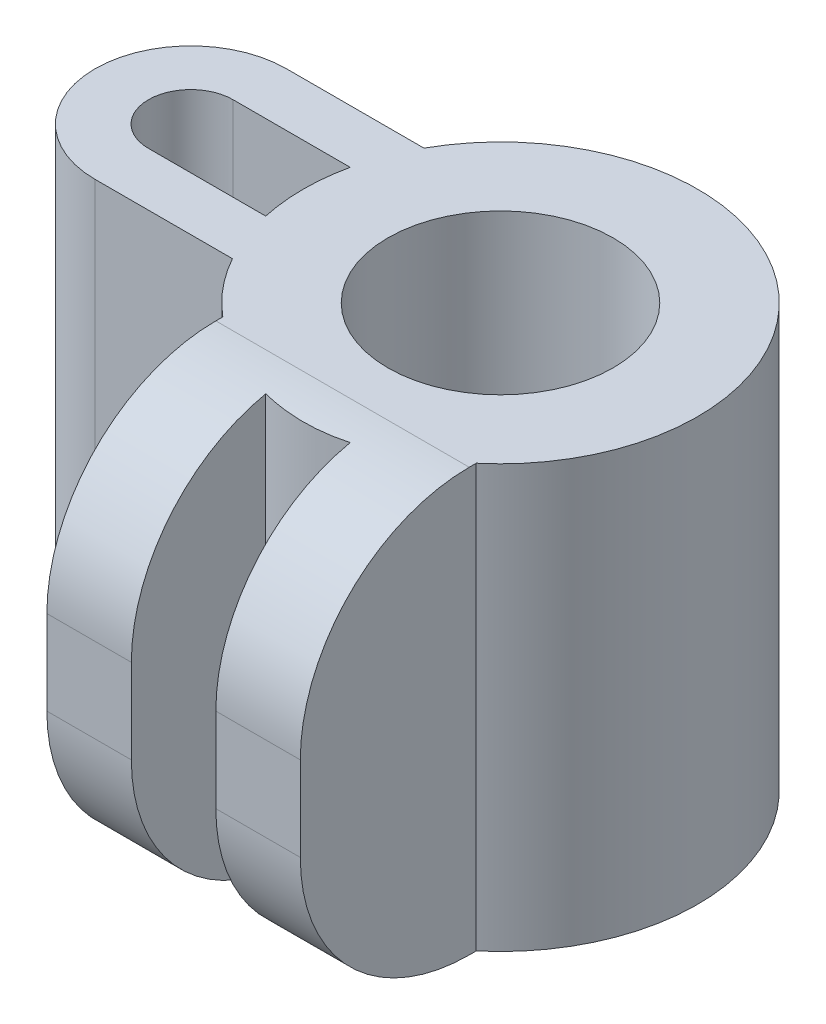
SolidWorks part; units mm, degrees
ref_plane "Front Plane" through (0, 0, 0) normal (0, 0, 1) x (1, 0, 0)
ref_plane "Top Plane" through (0, 0, 0) normal (0, 1, 0) x (1, 0, 0)
ref_plane "Right Plane" through (0, 0, 0) normal (1, 0, 0) x (0, 0, -1)
sketch "Sketch1" plane through (0, 0, 0) normal (0, 1, 0) x (1, 0, 0)
  line L0 (-55, 7.5) -> (-34.187, 7.5)
  line L1 (-55, -7.5) -> (-34.187, -7.5)
  line L2 (-55, -17) -> (-30.5941, -17)
  line L3 (-55, 17) -> (-30.5941, 17)
  line L4 (-22.5, -58.0464) -> (-22.5, -26.8095)
  line L5 (-7.5, -58.0464) -> (-7.5, -34.187)
  line L6 (-22.5, -58.0464) -> (-7.5, -58.0464)
  line L8 (22.5, -58.0464) -> (22.5, -26.8095)
  line L9 (7.5, -58.0464) -> (7.5, -34.187)
  line L10 (22.5, -58.0464) -> (7.5, -58.0464)
  circle A0 centre (0, 0) radius 20
  circle A1 centre (0, 0) radius 35
  arc A2 (-55, 17) -> (-55, -17) centre (-55, 0) ccw
  arc A3 (-55, 7.5) -> (-55, -7.5) centre (-55, 0) ccw
  point P4 (-20.0898, -58.0464)
  point P19 (-162.0359, 19.6617)
  point P20 (-160.0599, 14.524)
  dimension "D1" = 55
  dimension "D2" = 70
  dimension "D3" = 40
  dimension "D7" = 7.5
  dimension "D8" = 17
  dimension "D6" = 15
extrude "Boss-Extrude6" add sketch "Sketch1" along normal blind 75 contours A1 L4 L6 L5 | A1 L9 L10 L8 | A1 A0 | A3 L0 A1 L3 A2 L2 L1
fillet "Fillet1" radius 30 2 edges at (-15, 0, 58.0464) (-15, 75, 58.0464)
